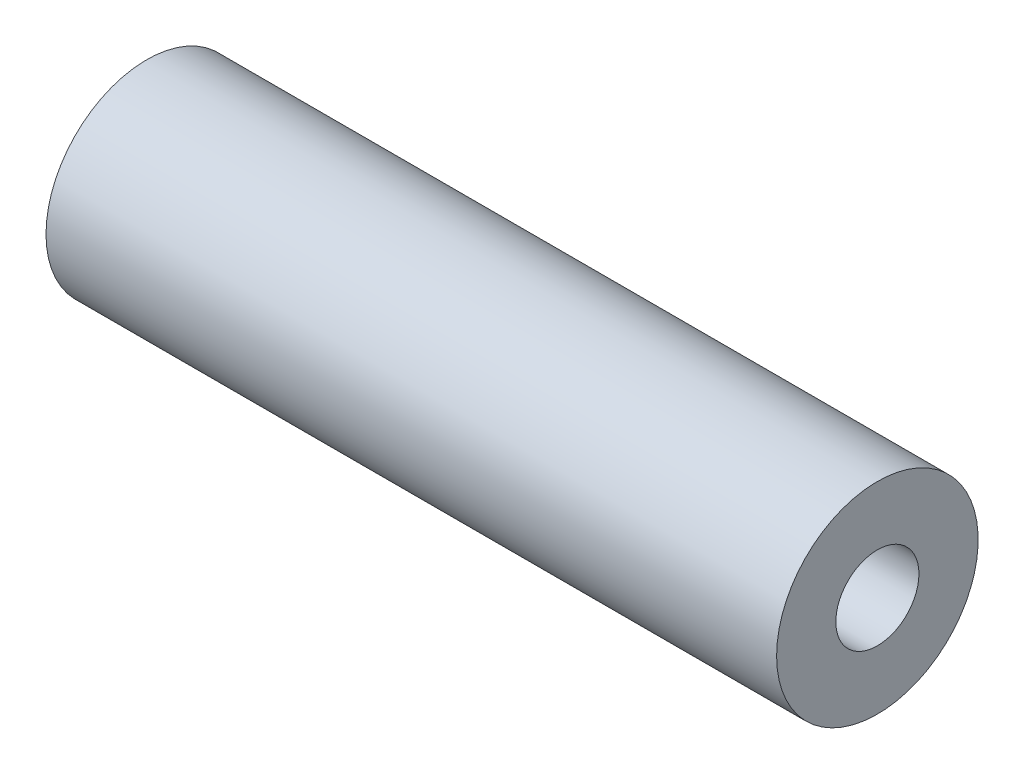
SolidWorks part; units mm, degrees
material "6061-T6 (SS)"
ref_plane "Front Plane" through (0, 0, 0) normal (0, 0, 1) x (1, 0, 0)
ref_plane "Top Plane" through (0, 0, 0) normal (0, 1, 0) x (1, 0, 0)
ref_plane "Right Plane" through (0, 0, 0) normal (1, 0, 0) x (0, 0, -1)
sketch "Sketch1" plane through (0, 0, 0) normal (1, 0, 0) x (0, 0, -1)
  circle A0 centre (0, 0) radius 4
  dimension "D1" = 8
extrude "Boss-Extrude1" add sketch "Sketch1" along normal mid plane 29
hole_wizard "M4 Tapped Hole1" positions "Sketch2" profile "Sketch3" tap size "M4" standard "ISO" end condition through all
sketch "Sketch2" plane through (14.5, 0, 0) normal (1, 0, 0) x (0, 0, -1)
  point P0 (0, 0)
sketch "Sketch3" plane through (14.5, 0, 0) normal (0, 1, 0) x (0, 0, -1)
  line L0 (0, 0) -> (0, 29)
  line L1 (0, 29) -> (1.65, 29)
  line L2 (1.65, 29) -> (1.65, 0)
  line L5 (1.65, 0) -> (0, 0)
  line L11 (0, -6.35) -> (0, 107.95) construction
  dimension "Thru Tap Drill Dia." = 3.3
  dimension "Thru Tap Drill Depth" = 29
cosmetic thread "Hole Thread1"
